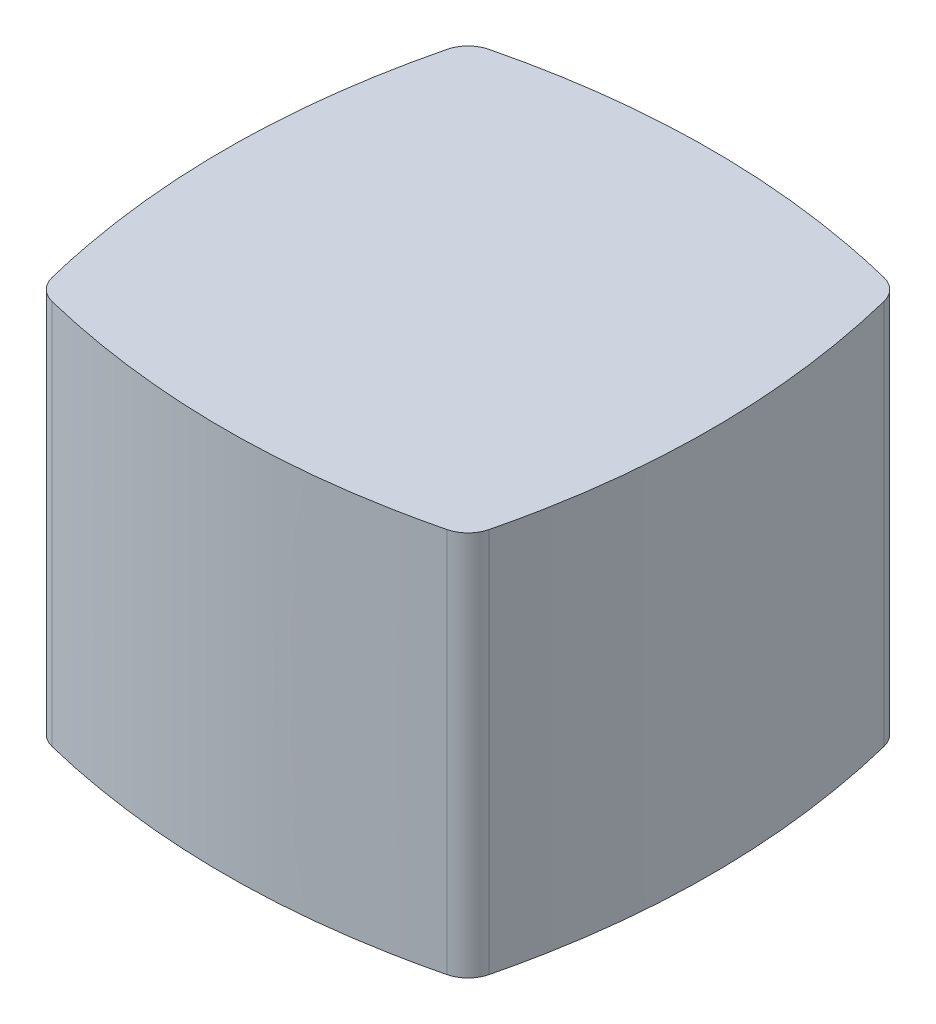
SolidWorks part; units mm, degrees
ref_plane "Front Plane" through (0, 0, 0) normal (0, 0, 1) x (1, 0, 0)
ref_plane "Top Plane" through (0, 0, 0) normal (0, 1, 0) x (1, 0, 0)
ref_plane "Right Plane" through (0, 0, 0) normal (1, 0, 0) x (0, 0, -1)
sketch "Sketch1" plane through (0, 0, 0) normal (0, 1, 0) x (1, 0, 0)
  line L0 (-26.9875, 0) -> (26.9875, 0)
  line L9 (-23.8125, -23.8125) -> (23.8125, 23.8125) construction
  line L10 (-23.8125, 23.8125) -> (23.8125, -23.8125) construction
  line L11 (0, 0) -> (-37.7304, 0) construction
  line L12 (-37.7304, 0) -> (0, 0) construction
  line L13 (0, 0) -> (0, 28.6183) construction
  line L14 (0, -26.9875) -> (0, 26.9875)
  spline S0 degree 2 poles (-23.8125, 23.8125) (-30.1625, 0) (-23.8125, -23.8125) knots 0 0 0 1 1 1
  spline S1 degree 2 poles (-23.8125, 23.8125) (0, 30.1625) (23.8125, 23.8125) knots 0 0 0 1 1 1
  spline S2 degree 2 poles (-23.8125, -23.8125) (0, -30.1625) (23.8125, -23.8125) knots 0 0 0 1 1 1
  spline S3 degree 2 poles (23.8125, 23.8125) (30.1625, 0) (23.8125, -23.8125) knots 0 0 0 1 1 1
  point P0 (0, 0)
  dimension "D1" = 47.625
  dimension "D2" = 47.625
  dimension "D3" = 26.9875
  dimension "D4" = 26.9875
extrude "Boss-Extrude1" add sketch "Sketch1" along normal blind 42.8625 contours S0 S2 L14 L0 | S1 S0 L0 L14 | S3 S1 L14 L0 | S3 L0 L14 S2
fillet "Fillet1" radius 3.175 4 edges at (-23.8125, 21.4312, -23.8125) (23.8125, 21.4312, -23.8125) (-23.8125, 21.4312, 23.8125) (23.8125, 21.4312, 23.8125)
shell "Shell1" thickness 2.54
